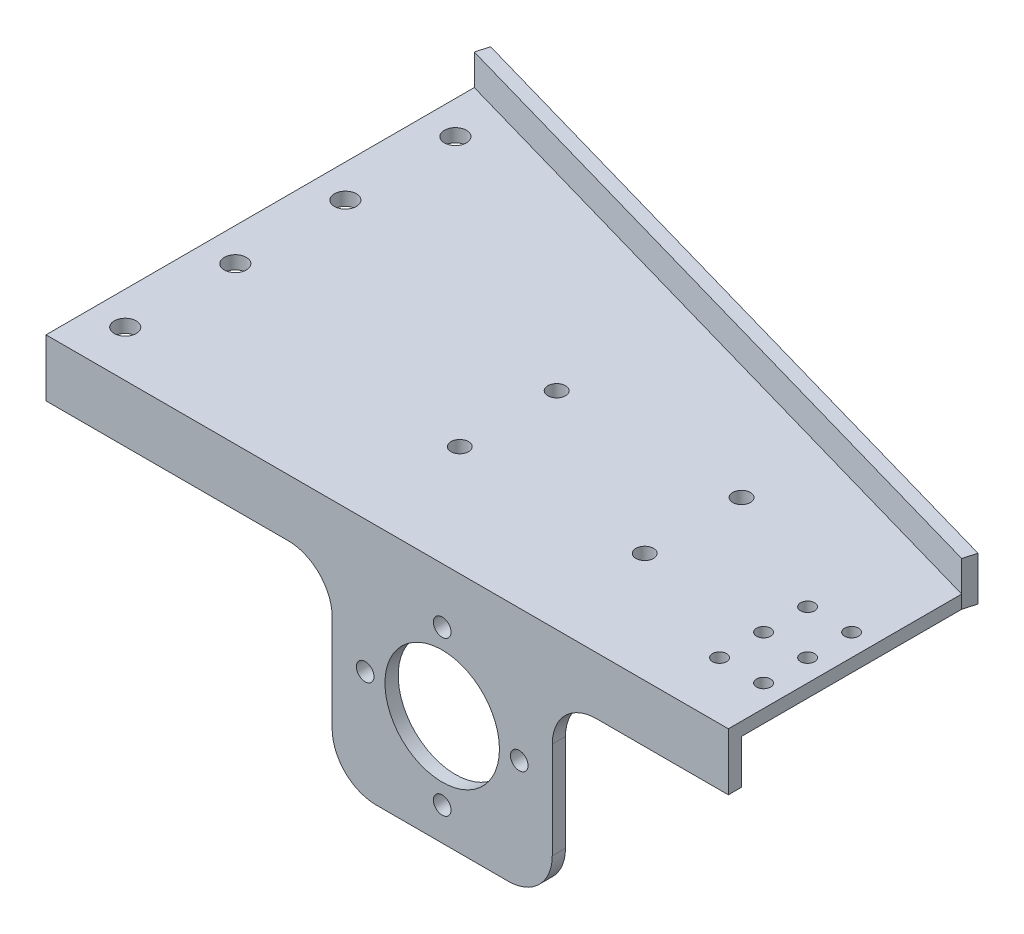
SolidWorks part; units mm, degrees
ref_plane "前视基准面" through (0, 0, 0) normal (0, 0, 1) x (1, 0, 0)
ref_plane "上视基准面" through (0, 0, 0) normal (0, 1, 0) x (1, 0, 0)
ref_plane "右视基准面" through (0, 0, 0) normal (1, 0, 0) x (0, 0, -1)
sketch "草图1" plane through (0, 0, 0) normal (0, 1, 0) x (1, 0, 0)
  line L0 (70, -45) -> (70, 5)
  line L1 (-85, 45) -> (70, 45)
  line L2 (-85, 45) -> (-85, -45)
  line L3 (-85, -45) -> (70, -45)
  line L4 (70, 45) -> (70, -45)
  line L5 (-85, 45) -> (70, -45) construction
  line L6 (-85, -45) -> (70, 45) construction
  line L7 (-70, 45) -> (70, 5)
  line L8 (-85, 45) -> (-70, 45)
  line L9 (-70, 45) -> (-85, 49.2857)
  line L10 (-85, 49.2857) -> (-85, 45)
  point P0 (0, 0)
extrude "凸台-拉伸1" add sketch "草图1" along normal blind 3 contours L7 L1 L2 L3 L0 | L9 L10 L1
hole_wizard "Ø5.0 (5) 直径孔2" positions "草图3" profile "草图2" hole size "Ø5.0" standard "GB" end condition through all
sketch "草图3" plane through (0, 3, 0) normal (0, 1, 0) x (1, 0, 0)
  line L0 (-85, -37.5) -> (-77.5, -37.5)
  line L1 (-85, 49.2857) -> (-85, -45) construction
  line L2 (-77.5, -37.5) -> (-77.5, -45)
  line L3 (-85, -45) -> (70, -45) construction
  line L4 (-77.5, -37.5) -> (-77.5, -12.5)
  line L7 (-77.5, 37.5) -> (-85, 37.5)
  line L9 (-77.5, 37.5) -> (-77.5, 12.5)
  point P2 (-77.5, -37.5)
  point P14 (-77.5, -12.5)
  point P20 (-77.5, 37.5)
  point P27 (-77.5, 12.5)
sketch "草图2" plane through (-77.5, 3, 37.5) normal (1, 0, 0) x (0, 0, 1)
  line L0 (0, 0) -> (0, 3)
  line L1 (0, 3) -> (2.5, 3)
  line L2 (2.5, 3) -> (2.5, 0)
  line L5 (2.5, 0) -> (0, 0)
  line L11 (0, -6.35) -> (0, 107.95) construction
  dimension "通孔孔直径" = 5
  dimension "通孔孔深度" = 3
hole_wizard "Ø3.2 (3.2) 直径孔2" positions "草图7" profile "草图6" hole size "Ø3.2" standard "GB" end condition through all
sketch "草图7" plane through (0, 0, 0) normal (0, -1, 0) x (-1, 0, 0)
  line L0 (-70, -35) -> (-65, -35)
  line L1 (-70, -45) -> (-70, 5) construction
  line L2 (-65, -35) -> (-65, -45)
  line L3 (85, -45) -> (-70, -45) construction
  point P2 (-65, -35)
sketch "草图6" plane through (65, 0, 35) normal (1, 0, 0) x (0, 0, -1)
  line L0 (0, 0) -> (0, 3)
  line L1 (0, 3) -> (1.6, 3)
  line L2 (1.6, 3) -> (1.6, 0)
  line L5 (1.6, 0) -> (0, 0)
  line L11 (0, -6.35) -> (0, 107.95) construction
  dimension "通孔孔直径" = 3.2
  dimension "通孔孔深度" = 3
pattern_linear "阵列(线性)1" count 3 spacing 10 along (0, 0, -1) count 2 spacing 10 along (-1, 0, 0) of "Ø3.2 (3.2) 直径孔2"
sketch "草图8" plane through (0, 3, 0) normal (0, 1, 0) x (1, 0, 0)
  line L0 (70, -45) -> (-85, -45)
  line L1 (-85, -45) -> (-85, -48)
  line L2 (-85, -48) -> (70, -48)
  line L3 (70, -48) -> (70, -45)
extrude "凸台-拉伸2" add sketch "草图8" against normal blind 13
sketch "草图10" plane through (0, 3, 0) normal (0, 1, 0) x (1, 0, 0)
  line L0 (70, -48) -> (30, -48)
  line L1 (-85, -48) -> (70, -48) construction
  line L2 (30, -48) -> (-20, -48)
  line L3 (-20, -48) -> (-20, -45)
  line L4 (-20, -45) -> (30, -45)
  line L5 (30, -45) -> (30, -48)
extrude "凸台-拉伸3" add sketch "草图10" against normal blind 55 contours L2 L3 L4 L5
sketch "草图11" plane through (0, 0, 0) normal (0, 1, 0) x (1, 0, 0)
  line L0 (-85, 49.2857) -> (-84.1758, 52.1703)
  line L1 (-84.1758, 52.1703) -> (70.8242, 7.8846)
  line L2 (70.8242, 7.8846) -> (70, 5)
  line L3 (70, 5) -> (-85, 49.2857)
extrude "凸台-拉伸5" add sketch "草图11" along normal blind 10
sketch "草图12" plane through (0, 0, 48) normal (0, 0, 1) x (1, 0, 0)
  line L0 (5, -52) -> (5, -27) construction
  line L1 (30, -52) -> (-20, -52) construction
  circle A0 centre (5, -27) radius 13
extrude "切除-拉伸1" cut sketch "草图12" against normal blind 3
sketch "草图13" plane through (0, 0, 48) normal (0, 0, 1) x (1, 0, 0)
  line L0 (5, -27) -> (5, -44.5) construction
  circle A0 centre (5, -44.5) radius 2
extrude "切除-拉伸2" cut sketch "草图13" against normal blind 3
pattern_circular "阵列(圆周)1" count 4 over 360 about axis through (5, -27, 0) along (0, 0, 1) of "切除-拉伸2"
fillet "圆角1" radius 10 4 edges at (-20, -10, 46.5) (-20, -52, 46.5) (30, -10, 46.5) (30, -52, 46.5)
hole_wizard "Ø4.0 (4) 直径孔1" positions "草图15" profile "草图14" hole size "Ø4.0" standard "GB" end condition through all
sketch "草图15" plane through (0, 0, 0) normal (0, -1, 0) x (-1, 0, 0)
  line L0 (85, -45) -> (85, -23)
  line L1 (85, 49.2857) -> (85, -45) construction
  line L2 (85, -23) -> (-5, -23)
  line L3 (-5, -23) -> (-5, -1)
  line L7 (-5, -1) -> (16, -1)
  line L9 (-5, -23) -> (-26, -23)
  point P13 (16, -1)
  point P17 (-26, -23)
  point P21 (16, -23)
  point P23 (-26, -1)
sketch "草图14" plane through (-16, 0, 1) normal (1, 0, 0) x (0, 0, -1)
  line L0 (0, 0) -> (0, 10)
  line L1 (0, 10) -> (2, 10)
  line L2 (2, 10) -> (2, 0)
  line L5 (2, 0) -> (0, 0)
  line L11 (0, -6.35) -> (0, 107.95) construction
  dimension "通孔孔直径" = 4
  dimension "通孔孔深度" = 10
